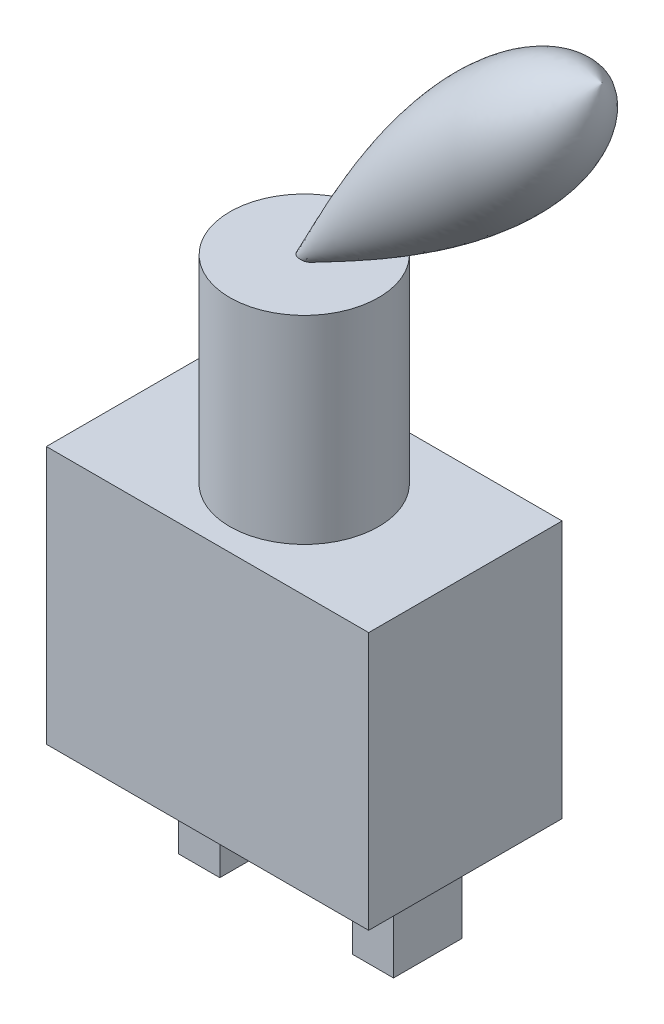
SolidWorks part; units mm, degrees
ref_plane "Front Plane" through (0, 0, 0) normal (0, 0, 1) x (1, 0, 0)
ref_plane "Top Plane" through (0, 0, 0) normal (0, 1, 0) x (1, 0, 0)
ref_plane "Right Plane" through (0, 0, 0) normal (1, 0, 0) x (0, 0, -1)
sketch "Sketch3" plane through (0, 0, 0) normal (0, 0, 1) x (1, 0, 0)
  line L1 (-6.5, -5.2) -> (6.5, -5.2)
  line L2 (-6.5, -5.2) -> (-6.5, 5.2)
  line L3 (-6.5, 5.2) -> (6.5, 5.2)
  line L4 (6.5, -5.2) -> (6.5, 5.2)
  line L5 (-6.5, -5.2) -> (6.5, 5.2) construction
  line L6 (-6.5, 5.2) -> (6.5, -5.2) construction
  point P0 (0, 0)
  dimension "D1" = 13
  dimension "D2" = 10.4
extrude "Boss-Extrude1" add sketch "Sketch3" along normal mid plane 7.8
sketch "Sketch4" plane through (0, 5.2, 0) normal (0, 1, 0) x (1, 0, 0)
  circle A0 centre (0, 0) radius 3
  dimension "D1" = 6
extrude "Boss-Extrude2" add sketch "Sketch4" along normal blind 8
ref_plane "Plane1" through (-6.6, 6.6, 0) normal (0.7071, -0.7071, 0) x (-0.7071, -0.7071, 0)
sketch "Sketch5" plane through (-6.6, 6.6, 0) normal (0.7071, -0.7071, 0) x (-0.7071, -0.7071, 0)
  line L0 (-9.3338, 0) -> (-50009.3338, 0) construction
  line L1 (-26.3017, 0) -> (-8.2873, 0)
  ellipse E1 centre (-9.3338, 0) end of major axis (-9.3338, 3) minor radius 2.1213
  ellipse E2 centre (-9.3338, 0) end of major axis (-9.3338, 3) minor radius 2.1213 construction
  spline S0 degree 3 poles (-8.2873, 0) (-9.6927, -0.0593) (-22.8047, -5.2575) (-26.3017, 0) knots 0 0 0 0 1 1 1 1
  point P4 (-8.2873, 0)
  point P17 (-26.3017, 0)
  point P19 (-25.7259, -1.1776)
  point P20 (-19.038, -3)
  point P21 (0, 0)
  point P22 (-26.1227, -0.2494)
  point P23 (0, 0)
  point P24 (-22.1115, -2.24)
  dimension "D1" = 0
revolve "Revolve1" add sketch "Sketch5" angle 360 about L0
sketch "Sketch6" plane through (0, -5.2, 0) normal (0, -1, 0) x (1, 0, 0)
  line L1 (-2.3399, -1.7004) -> (-4.0097, -1.7004)
  line L2 (-2.3399, -1.7004) -> (-2.3399, 1.064)
  line L3 (-2.3399, 1.064) -> (-4.0097, 1.064)
  line L4 (-4.0097, -1.7004) -> (-4.0097, 1.064)
  line L5 (-2.3399, -1.7004) -> (-4.0097, 1.064) construction
  line L6 (-2.3399, 1.064) -> (-4.0097, -1.7004) construction
  line L7 (4.6652, -1.7004) -> (3.0162, -1.7004)
  line L8 (4.6652, -1.7004) -> (4.6652, 1.064)
  line L9 (4.6652, 1.064) -> (3.0162, 1.064)
  line L10 (3.0162, -1.7004) -> (3.0162, 1.064)
  line L11 (4.6652, -1.7004) -> (3.0162, 1.064) construction
  line L12 (4.6652, 1.064) -> (3.0162, -1.7004) construction
  point P0 (-3.1748, -0.3182)
  point P5 (3.8407, -0.3182)
extrude "Boss-Extrude3" add sketch "Sketch6" along normal blind 4
